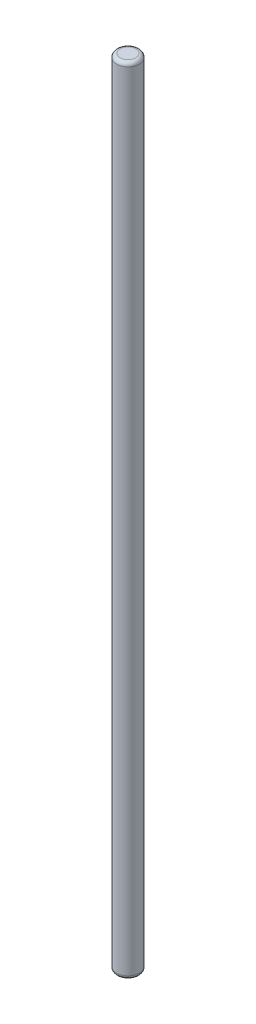
SolidWorks part; units mm, degrees
ref_plane "Front Plane" through (0, 0, 0) normal (0, 0, 1) x (1, 0, 0)
ref_plane "Top Plane" through (0, 0, 0) normal (0, 1, 0) x (1, 0, 0)
ref_plane "Right Plane" through (0, 0, 0) normal (1, 0, 0) x (0, 0, -1)
sketch "Sketch1" plane through (0, 0, 0) normal (0, 1, 0) x (1, 0, 0)
  circle A0 centre (0, 0) radius 2.3813
  dimension "D1" = 4.7625
extrude "Boss-Extrude1" add sketch "Sketch1" along normal blind 165.1
fillet "Fillet1" radius 0.762 2 edges at (0, 0, 2.3813) (0, 165.1, 2.3813)
